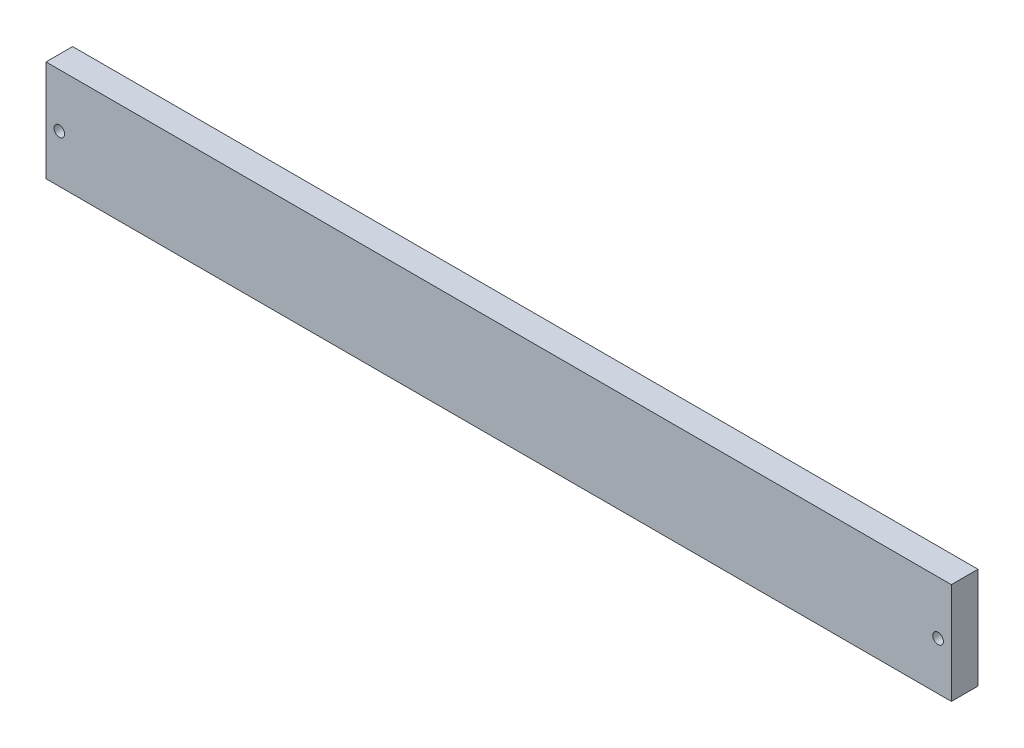
SolidWorks part; units mm, degrees
ref_plane "Plan de face" through (0, 0, 0) normal (0, 0, 1) x (1, 0, 0)
ref_plane "Plan de dessus" through (0, 0, 0) normal (0, 1, 0) x (1, 0, 0)
ref_plane "Plan de droite" through (0, 0, 0) normal (1, 0, 0) x (0, 0, -1)
sketch "Esquisse1" plane through (0, 0, 0) normal (0, 0, 1) x (1, 0, 0)
  line L1 (0, 0) -> (340, 0)
  line L2 (0, 0) -> (0, 38)
  line L3 (0, 38) -> (340, 38)
  line L4 (340, 0) -> (340, 38)
  dimension "D1" = 38
  dimension "D2" = 340
extrude "Boss.-Extru.1" add sketch "Esquisse1" along normal blind 10
sketch "Esquisse2" plane through (0, 0, 10) normal (0, 0, 1) x (1, 0, 0)
  line L0 (5, 38) -> (5, 0) construction
  line L1 (340, 38) -> (0, 38) construction
  line L2 (0, 0) -> (340, 0) construction
  line L3 (0, 38) -> (0, 0) construction
  line L4 (170, 0) -> (170, 38) construction
  line L5 (335, 38) -> (335, 0) construction
  circle A0 centre (5, 18) radius 2
  circle A1 centre (335, 18) radius 2
  dimension "D1" = 4
  dimension "D2" = 20
  dimension "D3" = 5
extrude "Enlèv. mat.-Extru.1" cut sketch "Esquisse2" against normal through all both and the other way through all
